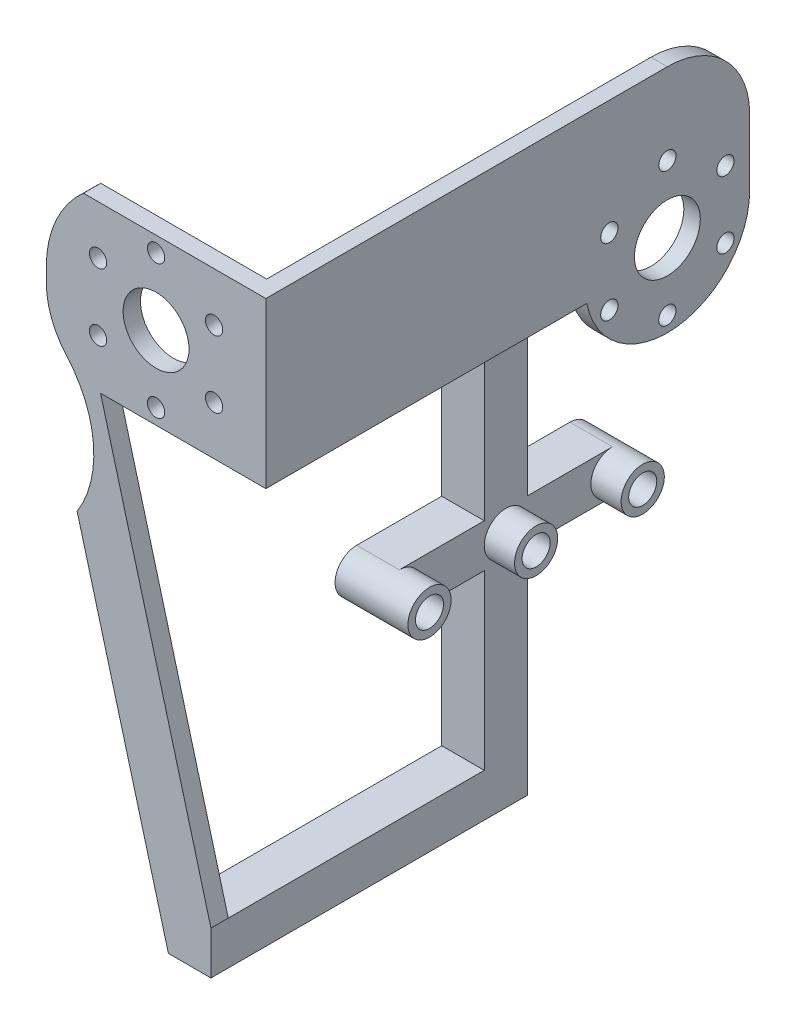
SolidWorks part; units mm, degrees
ref_plane "Front Plane" through (0, 0, 0) normal (0, 0, 1) x (1, 0, 0)
ref_plane "Top Plane" through (0, 0, 0) normal (0, 1, 0) x (1, 0, 0)
ref_plane "Right Plane" through (0, 0, 0) normal (1, 0, 0) x (0, 0, -1)
sketch "Sketch1" plane through (0, 0, 0) normal (0, 0, 1) x (1, 0, 0)
  line L1 (-25.4, -19.05) -> (25.4, -19.05)
  line L2 (-25.4, -19.05) -> (-25.4, 19.05)
  line L3 (-25.4, 19.05) -> (25.4, 19.05)
  line L4 (25.4, -19.05) -> (25.4, 19.05)
  line L5 (-25.4, -19.05) -> (25.4, 19.05) construction
  line L6 (-25.4, 19.05) -> (25.4, -19.05) construction
  circle A0 centre (0, 0) radius 15.5 construction
  circle A1 centre (0, 15.5) radius 2
  circle A2 centre (13.4234, 7.75) radius 2
  circle A3 centre (13.4234, -7.75) radius 2
  circle A4 centre (0, -15.5) radius 2
  circle A5 centre (-13.4234, -7.75) radius 2
  circle A6 centre (-13.4234, 7.75) radius 2
  circle A7 centre (0, 0) radius 7.62
  point P0 (0, 0)
  point P22 (0, 0)
  dimension "D2" = 31
  dimension "D3" = 4
  dimension "D5" = 15.24
  dimension "D1" = 38.1
  dimension "D6" = 50.8
  dimension "D4" = 6
extrude "Boss-Extrude1" add sketch "Sketch1" along normal blind 4
sketch "Sketch2" plane through (0, 0, 4) normal (0, 0, 1) x (1, 0, 0)
  line L2 (-16.8005, 19.05) -> (-25.4, 19.05)
  line L3 (-25.4, 19.05) -> (-25.4, 0)
  line L7 (25.4, 19.05) -> (-25.4, 19.05) construction
  arc A0 (-16.8005, 19.05) -> (-25.4, 0) centre (0, 0) ccw
extrude "Cut-Extrude1" cut sketch "Sketch2" against normal up to next
sketch "Sketch4" plane through (25.4, 0, 0) normal (1, 0, 0) x (0, 0, -1)
  line L0 (-4, -19.05) -> (0, -19.05) construction
  line L1 (-4, 19.05) -> (88.9, 19.05)
  line L2 (-4, 19.05) -> (-4, -19.05)
  line L3 (-4, -19.05) -> (88.9, -19.05)
  line L4 (88.9, 19.05) -> (88.9, -19.05)
  line L5 (0, -19.05) -> (0, 19.05) construction
  line L7 (107.95, 0) -> (69.85, 0)
  line L8 (107.95, 0) -> (107.95, -15.24)
  line L9 (107.95, -15.24) -> (69.85, -15.24)
  line L10 (69.85, 0) -> (69.85, -15.24)
  circle A0 centre (88.9, 0) radius 19.05
  circle A1 centre (88.9, -15.24) radius 19.05
  dimension "D1" = 88.9
  dimension "D2" = 15.24
extrude "Boss-Extrude2" add sketch "Sketch4" against normal blind 3.81 contours L2 L1 L4 L3 | A0 | L8 L7 L10 L9 | A1
sketch "Sketch5" plane through (25.4, 0, 0) normal (1, 0, 0) x (0, 0, -1)
  circle A0 centre (88.9, -15.24) radius 7.62
  circle A2 centre (88.9, -15.24) radius 15.5 construction
  circle A3 centre (88.9, 0.26) radius 2
  circle A4 centre (102.3234, -7.49) radius 2
  circle A5 centre (102.3234, -22.99) radius 2
  circle A6 centre (88.9, -30.74) radius 2
  circle A7 centre (75.4766, -22.99) radius 2
  circle A8 centre (75.4766, -7.49) radius 2
  arc A9 (70.2349, -19.05) -> (107.95, -15.24) centre (88.9, -15.24) ccw construction
  dimension "D1" = 15.24
  dimension "D2" = 31
  dimension "D3" = 4
  dimension "D4" = 6
extrude "Cut-Extrude2" cut sketch "Sketch5" against normal up to next
sketch "Sketch6" plane through (0, -19.05, 0) normal (0, -1, 0) x (1, 0, 0)
  line L0 (25.4, 4) -> (25.4, -70.2349) construction
  line L1 (25.4, -59.2349) -> (6.35, -59.2349)
  line L2 (25.4, -59.2349) -> (25.4, -69.2349)
  line L3 (25.4, -69.2349) -> (6.35, -69.2349)
  line L4 (6.35, -59.2349) -> (6.35, -69.2349)
  line L5 (25.4, -70.2349) -> (21.59, -70.2349) construction
  dimension "D1" = 10
  dimension "D2" = 19.05
  dimension "D3" = 1
extrude "Boss-Extrude3" add sketch "Sketch6" against normal blind 10
sketch "Sketch9" plane through (6.35, 0, 0) normal (-1, 0, 0) x (0, 0, 1)
  line L0 (-59.2349, -9.05) -> (-59.2349, -19.05) construction
  line L1 (-69.2349, -9.05) -> (-59.2349, -9.05)
  line L2 (-69.2349, -9.05) -> (-69.2349, -63.45)
  line L3 (-88.9, -73.45) -> (-39.5698, -73.45)
  line L4 (-59.2349, -9.05) -> (-59.2349, -63.45)
  line L5 (-64.2349, -9.05) -> (-64.2349, -73.45) construction
  line L6 (-88.9, -7.62) -> (-88.9, -22.86) construction
  line L7 (-59.2349, -63.45) -> (-39.5698, -63.45)
  line L8 (-64.2349, -63.45) -> (-64.2349, -73.45)
  line L9 (-64.2349, -73.45) -> (-39.5698, -73.45)
  line L11 (-69.2349, -63.45) -> (-88.9, -63.45)
  line L12 (-64.2349, -63.45) -> (-64.2349, -73.45)
  line L13 (-64.2349, -73.45) -> (-88.9, -73.45)
  circle A0 centre (-88.9, -15.24) radius 7.62 construction
  circle A1 centre (-64.2349, -68.45) radius 5 construction
  circle A2 centre (-64.2349, -68.45) radius 3.25
  arc A3 (-88.9, -63.45) -> (-88.9, -73.45) centre (-88.9, -68.45) ccw
  circle A4 centre (-88.9, -68.45) radius 3.25
  circle A5 centre (-39.5698, -68.45) radius 3.25
  arc A6 (-39.5698, -63.45) -> (-39.5698, -73.45) centre (-39.5698, -68.45) cw
  dimension "D2" = 10
  dimension "D3" = 6.5
  dimension "D1" = 58.21
extrude "Boss-Extrude6" add sketch "Sketch9" against normal blind 6.35 and the other way blind 3.5
sketch "Sketch10" plane through (12.7, 0, 0) normal (1, 0, 0) x (0, 0, -1)
  line L1 (64.2349, -19.05) -> (64.2349, -73.45) construction
  line L3 (69.2349, -63.45) -> (88.9, -63.45) construction
  line L4 (69.2349, -19.05) -> (59.2349, -19.05) construction
  circle A0 centre (64.2349, -68.45) radius 5
  circle A2 centre (64.2349, -68.45) radius 5 construction
  circle A4 centre (64.2349, -68.45) radius 3.25
  circle A5 centre (64.2349, -68.45) radius 3.25 construction
  circle A6 centre (39.5698, -68.45) radius 5
  circle A7 centre (88.9, -68.45) radius 5
  circle A8 centre (88.9, -68.45) radius 3.25 construction
  circle A9 centre (39.5698, -68.45) radius 3.25 construction
  circle A10 centre (88.9, -68.45) radius 3.25
  circle A11 centre (39.5698, -68.45) radius 3.25
  arc A12 (39.5698, -63.45) -> (39.5698, -73.45) centre (39.5698, -68.45) ccw construction
  arc A13 (88.9, -73.45) -> (88.9, -63.45) centre (88.9, -68.45) ccw construction
extrude "Boss-Extrude7" add sketch "Sketch10" along normal blind 7 contours A6 | A11 | A4 | A0 | A10 | A7
sketch "Sketch11" plane through (6.35, 0, 0) normal (-1, 0, 0) x (0, 0, 1)
  line L1 (-69.2349, -9.05) -> (-59.2349, -9.05)
  line L2 (-69.2349, -9.05) -> (-69.2349, -19.05)
  line L3 (-69.2349, -19.05) -> (-59.2349, -19.05)
  line L4 (-59.2349, -9.05) -> (-59.2349, -19.05)
extrude "Boss-Extrude8" add sketch "Sketch11" along normal up to surface (3.5 mm away) up to face at (2.85, -54.85, -64.2349)
sketch "Sketch12" plane through (2.85, 0, 0) normal (-1, 0, 0) x (0, 0, 1)
  line L0 (-88.9, -73.45) -> (-39.5698, -73.45) construction
  line L1 (-69.2349, -73.45) -> (-59.2349, -73.45)
  line L2 (-69.2349, -73.45) -> (-69.2349, -123.45)
  line L3 (-69.2349, -123.45) -> (-59.2349, -123.45)
  line L4 (-59.2349, -73.45) -> (-59.2349, -123.45)
  line L5 (-59.2349, -9.05) -> (-59.2349, -63.45) construction
  line L6 (-69.2349, -9.05) -> (-69.2349, -63.45) construction
  line L7 (4, 0) -> (4, 19.05) construction
  line L8 (-59.2349, -123.45) -> (4, -123.45)
  line L9 (-59.2349, -123.45) -> (-59.2349, -113.45)
  line L10 (-59.2349, -113.45) -> (4, -113.45)
  line L11 (4, -123.45) -> (4, -113.45)
  dimension "D1" = 50
extrude "Boss-Extrude9" add sketch "Sketch12" against normal up to surface (9.85 mm away) contours L9 L8 L11 L10 | L2 L1 L4 L3 up to face at (12.7, -58.07, -64.7349)
sketch "Sketch14" plane through (0, 0, 4) normal (0, 0, 1) x (1, 0, 0)
  line L0 (-25.4, -19.05) -> (2.85, -123.45)
  line L1 (2.85, -123.45) -> (12.7, -113.45)
  line L2 (12.7, -113.45) -> (-12.8441, -19.05)
  line L3 (-12.8441, -19.05) -> (-25.4, -19.05)
extrude "Boss-Extrude11" add sketch "Sketch14" against normal up to surface (4 mm away) up to face at (-5.2942, 0.1851, 0)
sketch "Sketch15" plane through (0, 0, 4) normal (0, 0, 1) x (1, 0, 0)
  line L0 (-25.4, 0) -> (-25.4, -19.05) construction
  line L1 (-12.8441, -19.05) -> (25.4, -19.05) construction
  line L2 (-25.4, -3.05) -> (-39.4, -3.05)
  line L3 (-39.4, -3.05) -> (-39.4, -7.05)
  arc A0 (-39.4, -7.05) -> (-20.7275, -15.4266) centre (-39.4, -32.05) ccw
  arc A1 (-25.4, -3.05) -> (-20.7275, -15.4266) centre (-6.9382, -3.1505) ccw
  circle A2 centre (0, 0) radius 7.62 construction
  point P1 (-25.4, -3.05)
  point P9 (-20.8119, -15.3323)
  point P10 (0, 0)
  dimension "D2" = 50
  dimension "D1" = 14
  dimension "D3" = 13
  dimension "D4" = 4
extrude "Cut-Extrude3" cut sketch "Sketch15" against normal up to surface (4 mm away) up to face at (-2.3239, -40.9416, 0)
equation "\"mounting distance\"= 24mm"
equation "\"ded\"= 2mm"
equation "\"rack base distance\"= 3mm"
equation "\"slot depth\"= 1.15in"
equation "\"stand height\"= \"mounting distance\" + \"ded\" + \"rack base distance\" + \"slot depth\""
equation "\"D1@Sketch9\"=\"stand height\""
